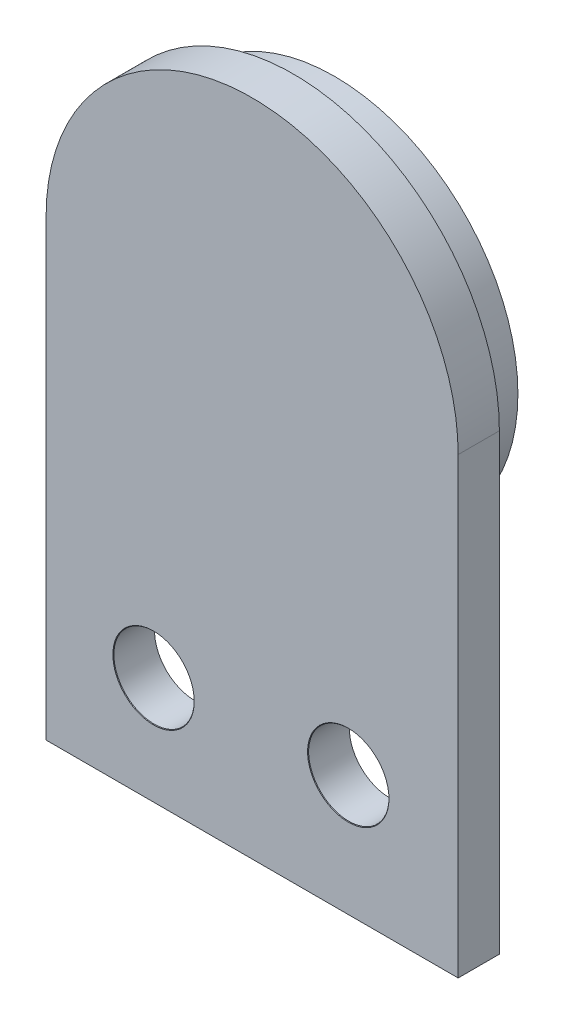
SolidWorks part; units mm, degrees
ref_plane "Front Plane" through (0, 0, 0) normal (0, 0, 1) x (1, 0, 0)
ref_plane "Top Plane" through (0, 0, 0) normal (0, 1, 0) x (1, 0, 0)
ref_plane "Right Plane" through (0, 0, 0) normal (1, 0, 0) x (0, 0, -1)
sketch "Sketch1" plane through (0, 0, 0) normal (0, 0, 1) x (1, 0, 0)
  line L0 (-10, 0) -> (-10, -22)
  line L1 (-10, -22) -> (10, -22)
  line L2 (10, -22) -> (10, 0)
  arc A0 (10, 0) -> (-10, 0) centre (0, 0) ccw
  dimension "D1" = 22
  dimension "D2" = 20
extrude "Boss-Extrude1" add sketch "Sketch1" along normal blind 2
sketch "Sketch2" plane through (0, 0, 0) normal (0, 0, -1) x (-1, 0, 0)
  circle A0 centre (0, 0) radius 8.9
  dimension "D1" = 17.8
extrude "Boss-Extrude2" add sketch "Sketch2" along normal blind 2
sketch "Sketch3" plane through (0, 0, -2) normal (0, 0, -1) x (-1, 0, 0)
  circle A0 centre (0, 0) radius 2
  dimension "D1" = 4
extrude "Boss-Extrude3" add sketch "Sketch3" along normal blind 3
hole_wizard "M3.5 Clearance Hole1" positions "Sketch4" profile "Sketch5" hole size "M3.5" standard "ANSI Metric" end condition through all
sketch "Sketch4" plane through (0, 0, 2) normal (0, 0, 1) x (1, 0, 0)
  point P0 (-4.7848, -16.7811)
  point P2 (4.6673, -16.141)
sketch "Sketch5" plane through (-4.7848, -16.7811, 2) normal (1, 0, 0) x (0, -1, 0)
  line L0 (0, 0) -> (0, 7)
  line L1 (0, 7) -> (1.95, 7)
  line L2 (1.95, 7) -> (1.95, 0.025)
  line L3 (1.95, 0.025) -> (1.975, 0)
  line L5 (1.975, 0) -> (0, 0)
  line L6 (-1.95, 0.025) -> (-1.975, 0) construction
  line L11 (0, -6.35) -> (0, 107.95) construction
  dimension "Thru Hole Dia." = 3.9
  dimension "Thru Hole Depth" = 7
  dimension "Near C'Sink Dia." = 3.95
  dimension "Near C'Sink Angle" = 90
